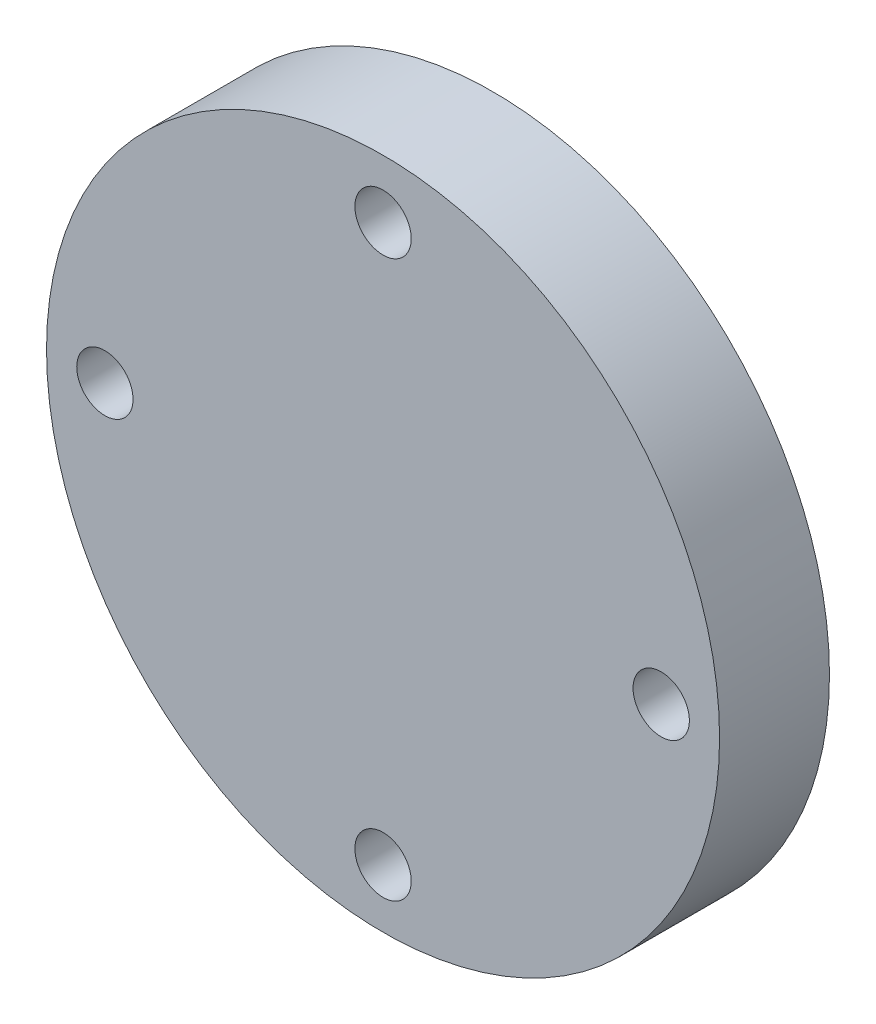
SolidWorks part; units mm, degrees
ref_plane "Front Plane" through (0, 0, 0) normal (0, 0, 1) x (1, 0, 0)
ref_plane "Top Plane" through (0, 0, 0) normal (0, 1, 0) x (1, 0, 0)
ref_plane "Right Plane" through (0, 0, 0) normal (1, 0, 0) x (0, 0, -1)
sketch "Sketch1" plane through (0, 0, 0) normal (0, 0, 1) x (1, 0, 0)
  circle A0 centre (0, 0) radius 24.5
  circle A1 centre (0, 0) radius 16
  dimension "D1" = 49
  dimension "D2" = 32
extrude "Boss-Extrude1" add sketch "Sketch1" along normal blind 3
sketch "Sketch2" plane through (0, 0, 3) normal (0, 0, 1) x (1, 0, 0)
  circle A0 centre (0, 0) radius 24.5
extrude "Boss-Extrude2" add sketch "Sketch2" along normal blind 5
sketch "Sketch3" plane through (0, 0, 0) normal (0, 0, -1) x (-1, 0, 0)
  circle A0 centre (0, 20.25) radius 2.05
  circle A1 centre (20.25, 0) radius 2.05
  circle A2 centre (0, -20.25) radius 2.05
  circle A3 centre (-20.25, 0) radius 2.05
  point P12 (0, 0)
  dimension "D1" = 4.1
  dimension "D2" = 20.25
  dimension "D3" = 4
extrude "Cut-Extrude1" cut sketch "Sketch3" against normal through all
sketch "Sketch4" plane through (0, 0, 3) normal (0, 0, -1) x (-1, 0, 0)
  circle A0 centre (0, 0) radius 1.5
  dimension "D1" = 3
extrude "Cut-Extrude2" cut sketch "Sketch4" against normal blind 3
